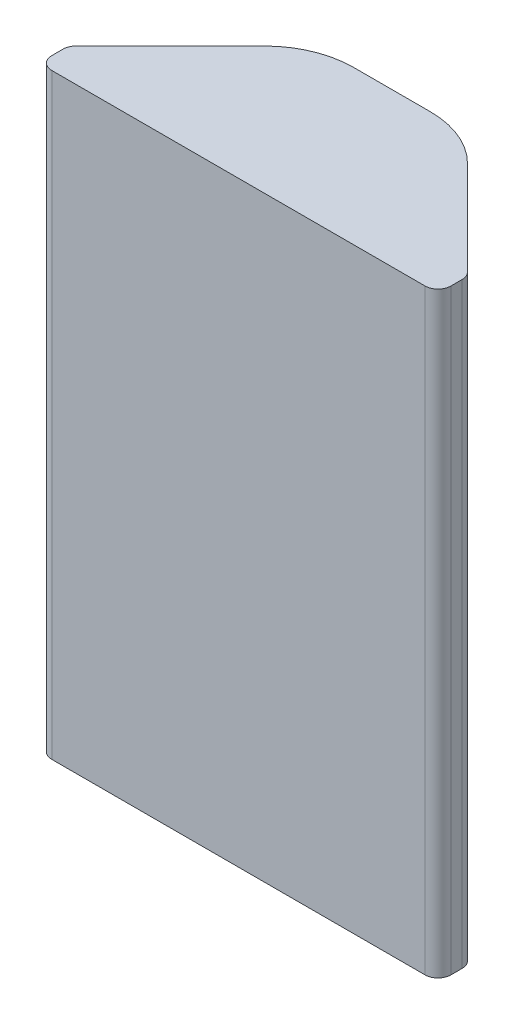
SolidWorks part; units mm, degrees
ref_plane "Front Plane" through (0, 0, 0) normal (0, 0, 1) x (1, 0, 0)
ref_plane "Top Plane" through (0, 0, 0) normal (0, 1, 0) x (1, 0, 0)
ref_plane "Right Plane" through (0, 0, 0) normal (1, 0, 0) x (0, 0, -1)
sketch "Sketch2" plane through (0, 0, 0) normal (0, 1, 0) x (1, 0, 0)
  line L104 (-14.3277, 0) -> (-9.4961, 0) construction
  line L105 (-7.9763, 0) -> (-5.6176, 0) construction
  line L106 (-4.064, 1.5536) -> (-4.064, 2.5104) construction
  line L107 (-5.6176, 4.064) -> (-9.3853, 4.064) construction
  line L108 (-10.287, 4.9657) -> (-10.287, 5.534) construction
  line L109 (-10.0229, 6.1716) -> (-5.2921, 10.9024) construction
  line L110 (-1.9335, 12.2936) -> (1.9335, 12.2936) construction
  line L111 (5.2921, 10.9024) -> (10.0229, 6.1716) construction
  line L112 (10.287, 5.534) -> (10.287, 4.9657) construction
  line L113 (9.3853, 4.064) -> (5.6176, 4.064) construction
  line L114 (4.064, 2.5104) -> (4.064, 1.5536) construction
  line L115 (5.6176, 0) -> (7.9763, 0) construction
  line L116 (9.4961, 0) -> (14.3277, 0) construction
  line L117 (19.05, 4.7223) -> (19.05, 9.5539) construction
  line L118 (19.05, 11.0737) -> (19.05, 13.4324) construction
  line L119 (17.4964, 14.986) -> (16.5396, 14.986) construction
  line L120 (14.986, 13.4324) -> (14.986, 9.6647) construction
  line L121 (14.0843, 8.763) -> (13.5524, 8.763) construction
  line L122 (12.9148, 9.0271) -> (8.144, 13.7978) construction
  line L123 (6.7564, 17.1478) -> (6.7564, 20.9522) construction
  line L124 (8.144, 24.3022) -> (12.9148, 29.0729) construction
  line L125 (13.5524, 29.337) -> (14.0843, 29.337) construction
  line L126 (14.986, 28.4353) -> (14.986, 24.6676) construction
  line L127 (16.5396, 23.114) -> (17.4964, 23.114) construction
  line L128 (19.05, 24.6676) -> (19.05, 27.0263) construction
  line L129 (19.05, 28.5461) -> (19.05, 33.3777) construction
  line L130 (14.3277, 38.1) -> (9.4961, 38.1) construction
  line L131 (7.9763, 38.1) -> (5.6176, 38.1) construction
  line L132 (4.064, 36.5464) -> (4.064, 35.5896) construction
  line L133 (5.6176, 34.036) -> (9.3853, 34.036) construction
  line L134 (10.287, 33.1343) -> (10.287, 32.566) construction
  line L135 (10.0229, 31.9284) -> (5.2921, 27.1976) construction
  line L136 (1.9335, 25.8064) -> (-1.9335, 25.8064) construction
  line L137 (-5.2921, 27.1976) -> (-10.0229, 31.9284) construction
  line L138 (-10.287, 32.566) -> (-10.287, 33.1343) construction
  line L139 (-9.3853, 34.036) -> (-5.6176, 34.036) construction
  line L140 (-4.064, 35.5896) -> (-4.064, 36.5464) construction
  line L141 (-5.6176, 38.1) -> (-7.9763, 38.1) construction
  line L142 (-9.4961, 38.1) -> (-14.3277, 38.1) construction
  line L143 (-19.05, 33.3777) -> (-19.05, 28.5482) construction
  line L144 (-19.05, 27.0242) -> (-19.05, 24.6676) construction
  line L145 (-17.4964, 23.114) -> (-16.5396, 23.114) construction
  line L146 (-14.986, 24.6676) -> (-14.986, 28.4353) construction
  line L147 (-14.0843, 29.337) -> (-13.5524, 29.337) construction
  line L148 (-12.9148, 29.0729) -> (-8.144, 24.3022) construction
  line L149 (-6.7564, 20.9522) -> (-6.7564, 17.1478) construction
  line L150 (-8.144, 13.7978) -> (-12.9148, 9.0271) construction
  line L151 (-13.5524, 8.763) -> (-14.0843, 8.763) construction
  line L152 (-14.986, 9.6647) -> (-14.986, 13.4324) construction
  line L153 (-16.5396, 14.986) -> (-17.4964, 14.986) construction
  line L154 (-19.05, 13.4324) -> (-19.05, 11.0758) construction
  line L155 (-19.05, 9.5518) -> (-19.05, 4.7223) construction
  arc A120 (-19.05, 3.2025) -> (-19.05, 4.7223) centre (-18.9933, 3.9624) ccw construction
  arc A121 (-19.05, 3.2025) -> (-15.8475, 0) centre (-15.8751, 3.1749) ccw construction
  arc A122 (-14.3277, 0) -> (-15.8475, 0) centre (-15.0876, 0.0567) ccw construction
  arc A123 (-7.9763, 0) -> (-9.4961, 0) centre (-8.7362, 0.0567) ccw construction
  arc A124 (-5.6176, 0) -> (-4.064, 1.5536) centre (-5.6176, 1.5536) ccw construction
  arc A125 (-4.064, 2.5104) -> (-5.6176, 4.064) centre (-5.6176, 2.5104) ccw construction
  arc A126 (-10.287, 4.9657) -> (-9.3853, 4.064) centre (-9.3853, 4.9657) ccw construction
  arc A127 (-10.0229, 6.1716) -> (-10.287, 5.534) centre (-9.3853, 5.534) ccw construction
  arc A128 (-1.9335, 12.2936) -> (-5.2921, 10.9024) centre (-1.9335, 7.5438) ccw construction
  arc A129 (5.2921, 10.9024) -> (1.9335, 12.2936) centre (1.9335, 7.5438) ccw construction
  arc A130 (10.287, 5.534) -> (10.0229, 6.1716) centre (9.3853, 5.534) ccw construction
  arc A131 (9.3853, 4.064) -> (10.287, 4.9657) centre (9.3853, 4.9657) ccw construction
  arc A132 (5.6176, 4.064) -> (4.064, 2.5104) centre (5.6176, 2.5104) ccw construction
  arc A133 (4.064, 1.5536) -> (5.6176, 0) centre (5.6176, 1.5536) ccw construction
  arc A134 (9.4961, 0) -> (7.9763, 0) centre (8.7362, 0.0567) ccw construction
  arc A135 (15.8475, 0) -> (14.3277, 0) centre (15.0876, 0.0567) ccw construction
  arc A136 (15.8475, 0) -> (19.05, 3.2025) centre (15.8751, 3.1749) ccw construction
  arc A137 (19.05, 4.7223) -> (19.05, 3.2025) centre (18.9933, 3.9624) ccw construction
  arc A138 (19.05, 11.0737) -> (19.05, 9.5539) centre (18.9933, 10.3138) ccw construction
  arc A139 (19.05, 13.4324) -> (17.4964, 14.986) centre (17.4964, 13.4324) ccw construction
  arc A140 (16.5396, 14.986) -> (14.986, 13.4324) centre (16.5396, 13.4324) ccw construction
  arc A141 (14.0843, 8.763) -> (14.986, 9.6647) centre (14.0843, 9.6647) ccw construction
  arc A142 (12.9148, 9.0271) -> (13.5524, 8.763) centre (13.5524, 9.6647) ccw construction
  arc A143 (6.7564, 17.1478) -> (8.144, 13.7978) centre (11.494, 17.1478) ccw construction
  arc A144 (8.144, 24.3022) -> (6.7564, 20.9522) centre (11.494, 20.9522) ccw construction
  arc A145 (13.5524, 29.337) -> (12.9148, 29.0729) centre (13.5524, 28.4353) ccw construction
  arc A146 (14.986, 28.4353) -> (14.0843, 29.337) centre (14.0843, 28.4353) ccw construction
  arc A147 (14.986, 24.6676) -> (16.5396, 23.114) centre (16.5396, 24.6676) ccw construction
  arc A148 (17.4964, 23.114) -> (19.05, 24.6676) centre (17.4964, 24.6676) ccw construction
  arc A149 (19.05, 28.5461) -> (19.05, 27.0263) centre (18.9933, 27.7862) ccw construction
  arc A150 (19.05, 34.8975) -> (19.05, 33.3777) centre (18.9933, 34.1376) ccw construction
  arc A151 (19.05, 34.8975) -> (15.8475, 38.1) centre (15.8751, 34.9251) ccw construction
  arc A152 (14.3277, 38.1) -> (15.8475, 38.1) centre (15.0876, 38.0433) ccw construction
  arc A153 (7.9763, 38.1) -> (9.4961, 38.1) centre (8.7362, 38.0433) ccw construction
  arc A154 (5.6176, 38.1) -> (4.064, 36.5464) centre (5.6176, 36.5464) ccw construction
  arc A155 (4.064, 35.5896) -> (5.6176, 34.036) centre (5.6176, 35.5896) ccw construction
  arc A156 (10.287, 33.1343) -> (9.3853, 34.036) centre (9.3853, 33.1343) ccw construction
  arc A157 (10.0229, 31.9284) -> (10.287, 32.566) centre (9.3853, 32.566) ccw construction
  arc A158 (1.9335, 25.8064) -> (5.2921, 27.1976) centre (1.9335, 30.5562) ccw construction
  arc A159 (-5.2921, 27.1976) -> (-1.9335, 25.8064) centre (-1.9335, 30.5562) ccw construction
  arc A160 (-10.287, 32.566) -> (-10.0229, 31.9284) centre (-9.3853, 32.566) ccw construction
  arc A161 (-9.3853, 34.036) -> (-10.287, 33.1343) centre (-9.3853, 33.1343) ccw construction
  arc A162 (-5.6176, 34.036) -> (-4.064, 35.5896) centre (-5.6176, 35.5896) ccw construction
  arc A163 (-4.064, 36.5464) -> (-5.6176, 38.1) centre (-5.6176, 36.5464) ccw construction
  arc A164 (-9.4961, 38.1) -> (-7.9763, 38.1) centre (-8.7362, 38.0433) ccw construction
  arc A165 (-15.8475, 38.1) -> (-14.3277, 38.1) centre (-15.0876, 38.0433) ccw construction
  arc A166 (-15.8475, 38.1) -> (-19.05, 34.8975) centre (-15.8751, 34.9251) ccw construction
  arc A167 (-19.05, 33.3777) -> (-19.05, 34.8975) centre (-18.9933, 34.1376) ccw construction
  arc A168 (-19.05, 27.0242) -> (-19.05, 28.5482) centre (-19.05, 27.7862) ccw construction
  arc A169 (-19.05, 24.6676) -> (-17.4964, 23.114) centre (-17.4964, 24.6676) ccw construction
  arc A170 (-16.5396, 23.114) -> (-14.986, 24.6676) centre (-16.5396, 24.6676) ccw construction
  arc A171 (-14.0843, 29.337) -> (-14.986, 28.4353) centre (-14.0843, 28.4353) ccw construction
  arc A172 (-12.9148, 29.0729) -> (-13.5524, 29.337) centre (-13.5524, 28.4353) ccw construction
  arc A173 (-6.7564, 20.9522) -> (-8.144, 24.3022) centre (-11.494, 20.9522) ccw construction
  arc A174 (-8.144, 13.7978) -> (-6.7564, 17.1478) centre (-11.494, 17.1478) ccw construction
  arc A175 (-13.5524, 8.763) -> (-12.9148, 9.0271) centre (-13.5524, 9.6647) ccw construction
  arc A176 (-14.986, 9.6647) -> (-14.0843, 8.763) centre (-14.0843, 9.6647) ccw construction
  arc A177 (-14.986, 13.4324) -> (-16.5396, 14.986) centre (-16.5396, 13.4324) ccw construction
  arc A178 (-17.4964, 14.986) -> (-19.05, 13.4324) centre (-17.4964, 13.4324) ccw construction
  arc A179 (-19.05, 9.5518) -> (-19.05, 11.0758) centre (-19.05, 10.3138) ccw construction
sketch "Sketch3" plane through (0, 0, 0) normal (0, 1, 0) x (1, 0, 0)
  line L8 (-5.6176, 4.318) -> (5.6176, 4.318)
  line L14 (9.3853, 4.318) -> (5.6176, 4.318)
  line L15 (10.033, 5.534) -> (10.033, 4.9657)
  line L16 (5.1125, 10.7228) -> (9.8433, 5.992)
  line L17 (-1.9335, 12.0396) -> (1.9335, 12.0396)
  line L18 (-9.8433, 5.992) -> (-5.1125, 10.7228)
  line L19 (-10.033, 4.9657) -> (-10.033, 5.534)
  line L20 (-5.6176, 4.318) -> (-9.3853, 4.318)
  line L21 (9.3853, 4.318) -> (5.6176, 4.318)
  line L22 (10.033, 5.534) -> (10.033, 4.9657)
  line L23 (5.1125, 10.7228) -> (9.8433, 5.992)
  line L24 (-1.9335, 12.0396) -> (1.9335, 12.0396)
  line L25 (-9.8433, 5.992) -> (-5.1125, 10.7228)
  line L26 (-10.033, 4.9657) -> (-10.033, 5.534)
  line L27 (-5.6176, 4.318) -> (-9.3853, 4.318)
  arc A12 (9.3853, 4.318) -> (10.033, 4.9657) centre (9.3853, 4.9657) ccw
  arc A13 (10.033, 5.534) -> (9.8433, 5.992) centre (9.3853, 5.534) ccw
  arc A14 (5.1125, 10.7228) -> (1.9335, 12.0396) centre (1.9335, 7.5438) ccw
  arc A15 (-1.9335, 12.0396) -> (-5.1125, 10.7228) centre (-1.9335, 7.5438) ccw
  arc A16 (-9.8433, 5.992) -> (-10.033, 5.534) centre (-9.3853, 5.534) ccw
  arc A17 (-10.033, 4.9657) -> (-9.3853, 4.318) centre (-9.3853, 4.9657) ccw
  arc A18 (9.3853, 4.318) -> (10.033, 4.9657) centre (9.3853, 4.9657) ccw
  arc A19 (10.033, 5.534) -> (9.8433, 5.992) centre (9.3853, 5.534) ccw
  arc A20 (5.1125, 10.7228) -> (1.9335, 12.0396) centre (1.9335, 7.5438) ccw
  arc A21 (-1.9335, 12.0396) -> (-5.1125, 10.7228) centre (-1.9335, 7.5438) ccw
  arc A22 (-9.8433, 5.992) -> (-10.033, 5.534) centre (-9.3853, 5.534) ccw
  arc A23 (-10.033, 4.9657) -> (-9.3853, 4.318) centre (-9.3853, 4.9657) ccw
  dimension "D1" = 0.254
extrude "Boss-Extrude1" add sketch "Sketch3" along normal mid plane 30
